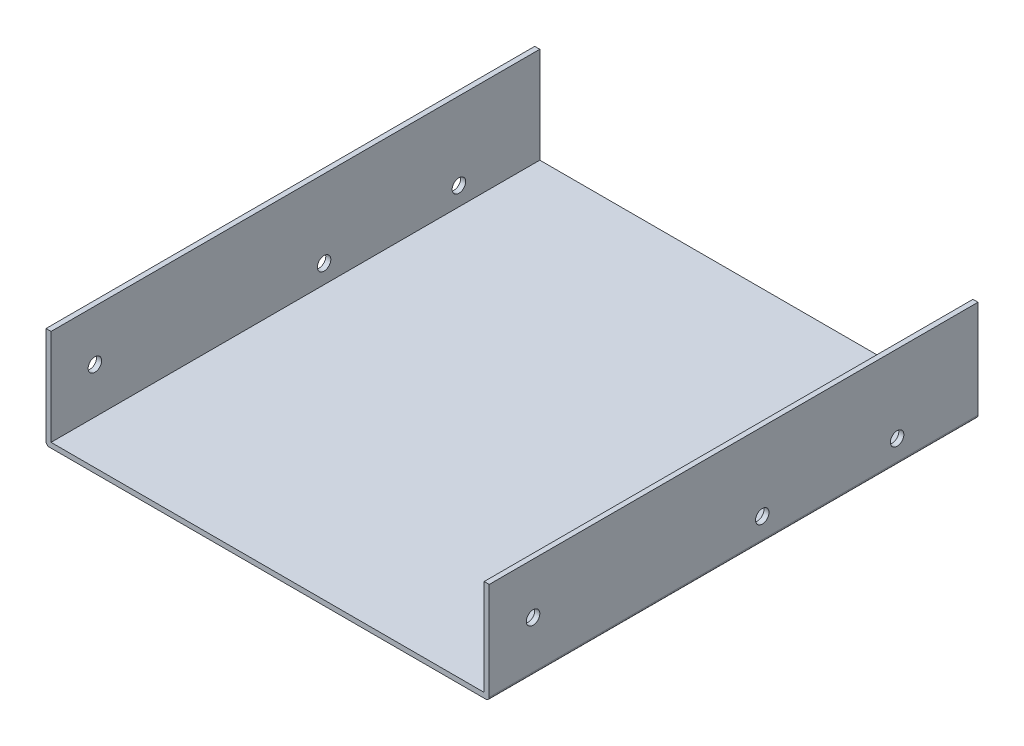
SolidWorks part; units mm, degrees
ref_plane "Alzado" through (0, 0, 0) normal (0, 0, 1) x (1, 0, 0)
ref_plane "Planta" through (0, 0, 0) normal (0, 1, 0) x (1, 0, 0)
ref_plane "Vista lateral" through (0, 0, 0) normal (1, 0, 0) x (0, 0, -1)
sketch "Croquis1" plane through (0, 0, 0) normal (0, 0, 1) x (1, 0, 0)
  line L0 (-64.25, 14.5) -> (-64.25, -14)
  line L1 (-65.75, 14.5) -> (-64.25, 14.5)
  line L2 (-65.75, 14.5) -> (-65.75, -14.5)
  line L3 (-64.75, -15.5) -> (64.75, -15.5)
  line L4 (65.75, 14.5) -> (65.75, -14.5)
  line L5 (-64.25, -14) -> (64.25, -14)
  line L6 (64.25, -14) -> (64.25, 14.5)
  line L7 (64.25, 14.5) -> (65.75, 14.5)
  line L8 (55, 0) -> (-55, 0) construction
  line L9 (0, -55) -> (0, 55) construction
  arc A0 (64.75, -15.5) -> (65.75, -14.5) centre (64.75, -14.5) ccw
  arc A1 (-65.75, -14.5) -> (-64.75, -15.5) centre (-64.75, -14.5) ccw
  point P8 (-65.75, 0)
  point P9 (65.75, 0)
  point P12 (0, -15.5)
  point P17 (65.75, -15.5)
  point P20 (-65.75, -15.5)
  dimension "D6" = 1
  dimension "D7" = 1
  dimension "D1" = 131.5
  dimension "D2" = 30
  dimension "D3" = 1.5
  dimension "D4" = 1.5
  dimension "D5" = 1.5
extrude "Saliente-Extruir1" add sketch "Croquis1" along normal mid plane 145
sketch "Croquis2" plane through (65.75, 0, 0) normal (1, 0, 0) x (0, 0, -1)
  line L0 (-72.5, -0.5) -> (-59.5, -0.5) construction
  line L1 (-72.5, -14.5) -> (-72.5, 14.5) construction
  line L2 (-59.5, -0.5) -> (-59.5, 14.5) construction
  line L3 (-72.5, 14.5) -> (72.5, 14.5) construction
  line L4 (72.5, -14.5) -> (72.5, 14.5) construction
  circle A0 centre (-59.5, -0.5) radius 2
  circle A1 centre (8.5, -8.5) radius 2
  circle A2 centre (48.5, -8.5) radius 2
  point P8 (8.5, -8.5)
  point P9 (48.5, -8.5)
  dimension "D3" = 23
  dimension "D7" = 4
  dimension "D8" = 4
  dimension "D9" = 4
  dimension "D1" = 13
  dimension "D2" = 15
  dimension "D4" = 23
  dimension "D5" = 24
  dimension "D6" = 40
extrude "Cortar-Extruir1" cut sketch "Croquis2" against normal blind 145
